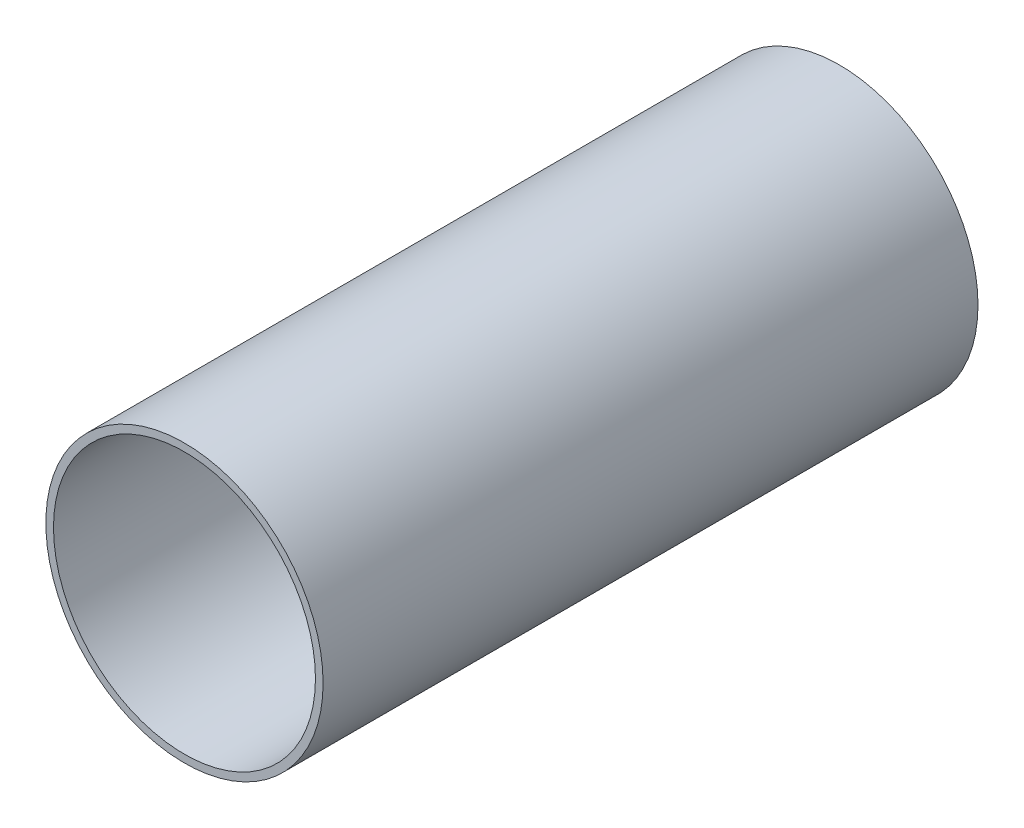
SolidWorks part; units mm, degrees
ref_plane "Front Plane" through (0, 0, 0) normal (0, 0, 1) x (1, 0, 0)
ref_plane "Top Plane" through (0, 0, 0) normal (0, 1, 0) x (1, 0, 0)
ref_plane "Right Plane" through (0, 0, 0) normal (1, 0, 0) x (0, 0, -1)
sketch "Sketch1" plane through (0, 0, 0) normal (0, 0, 1) x (1, 0, 0)
  circle A0 centre (0, 0) radius 6.35
  circle A1 centre (0, 0) radius 6
  dimension "D1" = 12.7
  dimension "D2" = 12
extrude "Boss-Extrude1" add sketch "Sketch1" along normal blind 30
